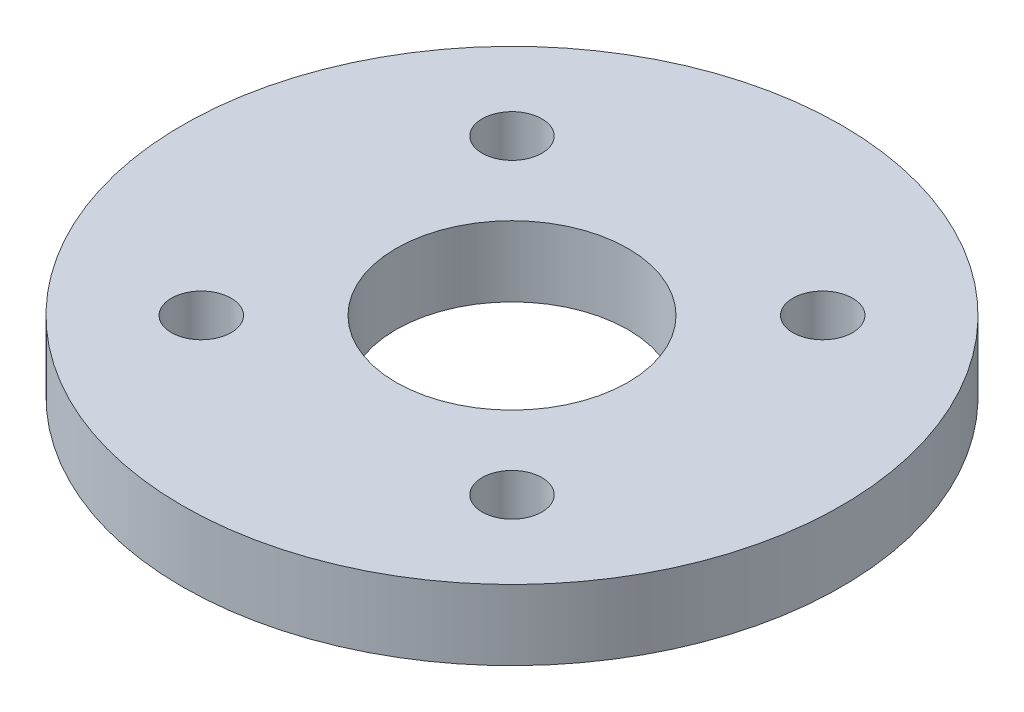
SolidWorks part; units mm, degrees
ref_plane "Front Plane" through (0, 0, 0) normal (0, 0, 1) x (1, 0, 0)
ref_plane "Top Plane" through (0, 0, 0) normal (0, 1, 0) x (1, 0, 0)
ref_plane "Right Plane" through (0, 0, 0) normal (1, 0, 0) x (0, 0, -1)
sketch "Sketch1" plane through (0, 0, 0) normal (0, 1, 0) x (1, 0, 0)
  line L1 (8.8388, 8.8388) -> (-8.8388, 8.8388) construction
  line L2 (-8.8388, 8.8388) -> (-8.8388, -8.8388) construction
  line L3 (-8.8388, -8.8388) -> (8.8388, -8.8388) construction
  line L4 (8.8388, -8.8388) -> (8.8388, 8.8388) construction
  circle A0 centre (0, 0) radius 18.75
  circle A1 centre (0, 0) radius 12.5 construction
  circle A2 centre (-8.8388, 8.8388) radius 1.7
  circle A3 centre (-8.8388, -8.8388) radius 1.7
  circle A4 centre (8.8388, -8.8388) radius 1.7
  circle A5 centre (8.8388, 8.8388) radius 1.7
  circle A6 centre (0, 0) radius 6.6
  dimension "D1" = 25
  dimension "D2" = 3.4
  dimension "D3" = 37.5
  dimension "D4" = 13.2
extrude "Boss-Extrude1" add sketch "Sketch1" along normal blind 4 contours A0 A5 L4 A4 L3 A3 L2 A2 L1 | A5 L1 A2 L2 A3 L3 A4 L4
